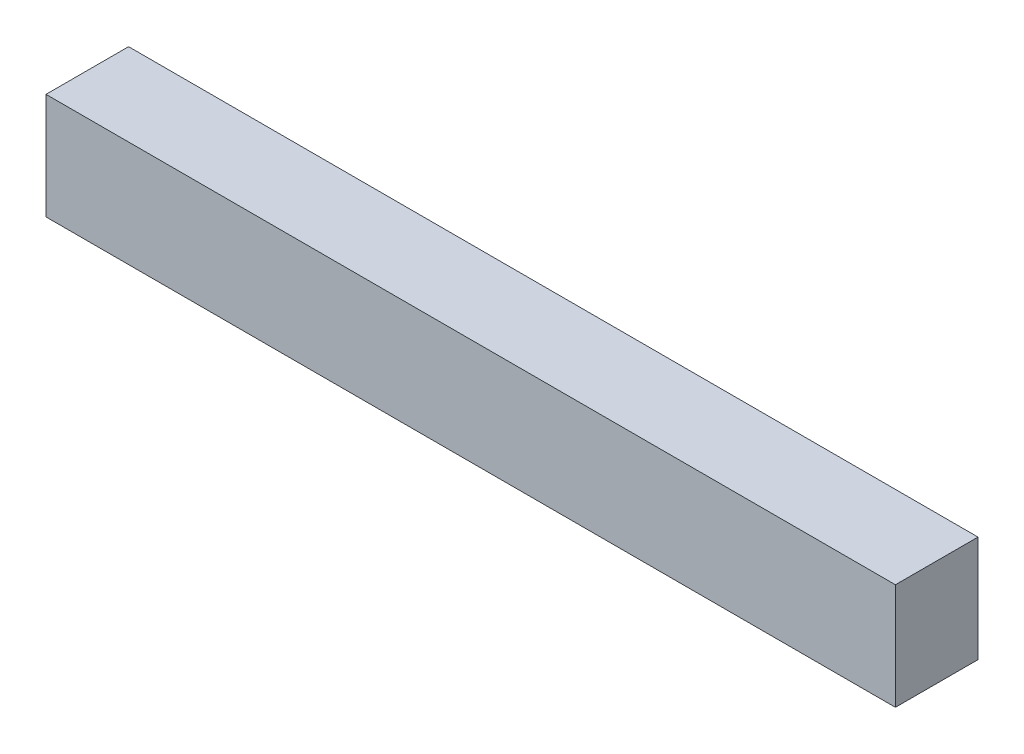
SolidWorks part; units mm, degrees
ref_plane "前视基准面" through (0, 0, 0) normal (0, 0, 1) x (1, 0, 0)
ref_plane "上视基准面" through (0, 0, 0) normal (0, 1, 0) x (1, 0, 0)
ref_plane "右视基准面" through (0, 0, 0) normal (1, 0, 0) x (0, 0, -1)
other "Configuration Table"
sketch "草图1" plane through (0, 0, 0) normal (0, 0, 1) x (1, 0, 0)
  line L1 (-180, -22.5) -> (180, -22.5)
  line L2 (-180, -22.5) -> (-180, 22.5)
  line L3 (-180, 22.5) -> (180, 22.5)
  line L4 (180, -22.5) -> (180, 22.5)
  line L5 (-180, -22.5) -> (180, 22.5) construction
  line L6 (-180, 22.5) -> (180, -22.5) construction
  point P0 (0, 0)
extrude "凸台-拉伸1" add sketch "草图1" along normal blind 35
